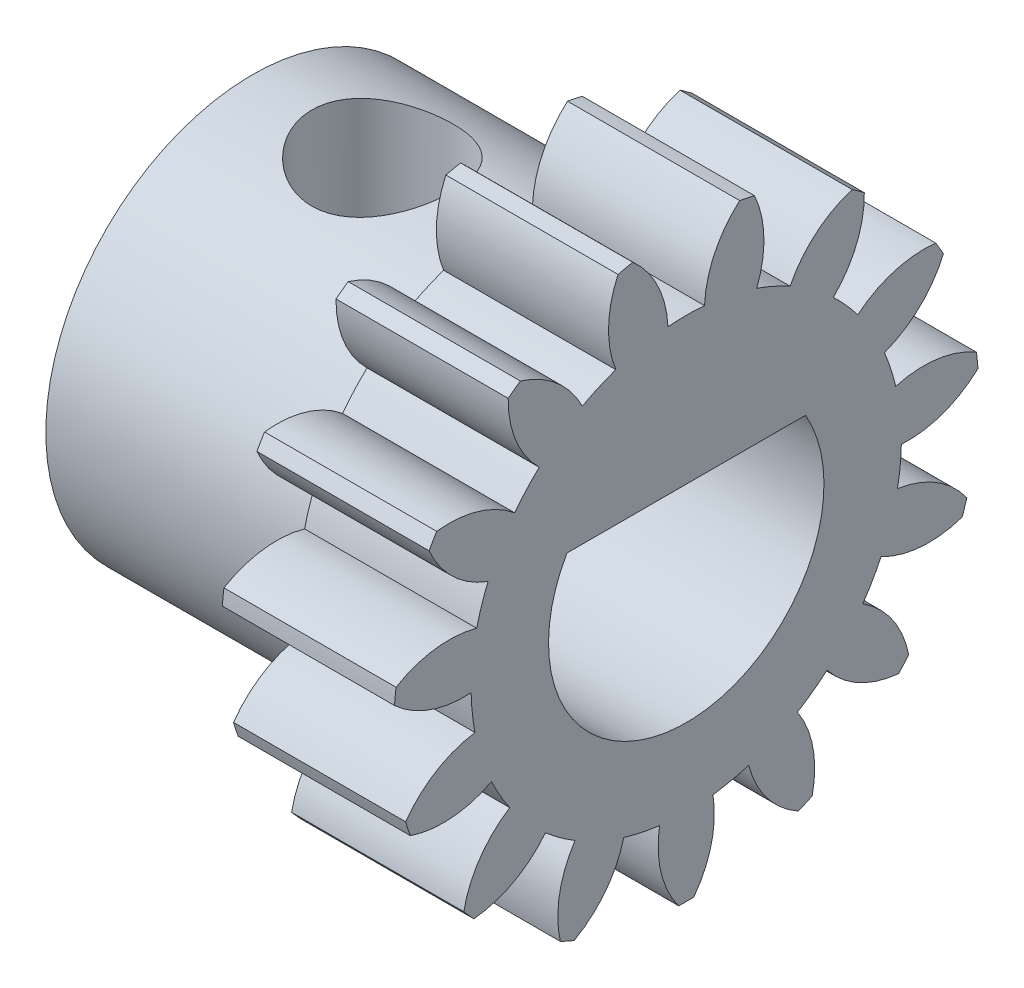
SolidWorks part; units mm, degrees
material "Plain Carbon Steel"
ref_plane "Front Plane" through (0, 0, 0) normal (0, 0, 1) x (1, 0, 0)
ref_plane "Top Plane" through (0, 0, 0) normal (0, 1, 0) x (1, 0, 0)
ref_plane "Right Plane" through (0, 0, 0) normal (1, 0, 0) x (0, 0, -1)
ref_plane "Plane1" through (0, 0, 0) normal (0, 0, -1) x (-1, 0, 0)
sketch "Sketch1" plane through (0, 0, 0) normal (0, 0, -1) x (-1, 0, 0)
  line L0 (-2.5, 4.25) -> (-2.5, 0)
  line L1 (-2.5, 0) -> (0, 0)
  line L2 (0, 0) -> (0, 4.25)
  line L3 (0, 4.25) -> (-2.5, 4.25)
  line L4 (-2.5, 0) -> (0, 0) construction
revolve "Revolve1" add sketch "Sketch1" angle 360 about L4
sketch "Sketch2" plane through (2.5, 0, 0) normal (1, 0, 0) x (0, 0, -1)
  arc A0 (2.586, 3.3727) -> (2.1353, 2.2803) centre (1.0861, 3.3523) cw
  arc A1 (2.1353, 2.2803) -> (2.491, 1.8853) centre (0, 0) cw
  arc A2 (2.491, 1.8853) -> (3.6245, 2.2193) centre (3.4475, 0.7298) cw
  arc A3 (3.6245, 2.2193) -> (2.586, 3.3727) centre (0, 0) ccw
extrude "Cut-Extrude1" cut sketch "Sketch2" against normal through all
sketch "Sketch3" plane through (2.5, 0, 0) normal (1, 0, 0) x (0, 0, -1)
  arc A0 (3.7342, 2.0293) -> (2.8782, 1.2146) centre (2.3557, 2.6207) cw
  arc A1 (2.8782, 1.2146) -> (3.0425, 0.7091) centre (0, 0) cw
  arc A2 (3.0425, 0.7091) -> (4.2138, 0.5532) centre (3.4462, -0.7355) cw
  arc A3 (4.2138, 0.5532) -> (3.7342, 2.0293) centre (0, 0) ccw
extrude "Cut-Extrude2" cut sketch "Sketch3" against normal through all
sketch "Sketch4" plane through (2.5, 0, 0) normal (1, 0, 0) x (0, 0, -1)
  arc A0 (4.2368, 0.335) -> (3.1234, -0.0611) centre (3.218, 1.436) cw
  arc A1 (3.1234, -0.0611) -> (3.0678, -0.5897) centre (0, 0) cw
  arc A2 (3.0678, -0.5897) -> (4.0745, -1.2086) centre (2.8491, -2.0736) cw
  arc A3 (4.0745, -1.2086) -> (4.2368, 0.335) centre (0, 0) ccw
extrude "Cut-Extrude3" cut sketch "Sketch4" against normal through all
sketch "Sketch5" plane through (2.5, 0, 0) normal (1, 0, 0) x (0, 0, -1)
  arc A0 (4.0067, -1.4172) -> (2.8285, -1.3262) centre (3.5238, 0.0029) cw
  arc A1 (2.8285, -1.3262) -> (2.5628, -1.7865) centre (0, 0) cw
  arc A2 (2.5628, -1.7865) -> (3.2307, -2.7613) centre (1.7594, -3.0532) cw
  arc A3 (3.2307, -2.7613) -> (4.0067, -1.4172) centre (0, 0) ccw
extrude "Cut-Extrude4" cut sketch "Sketch5" against normal through all
sketch "Sketch6" plane through (2.5, 0, 0) normal (1, 0, 0) x (0, 0, -1)
  arc A0 (3.0839, -2.9244) -> (2.0446, -2.362) centre (3.2204, -1.4306) cw
  arc A1 (2.0446, -2.362) -> (1.6146, -2.6744) centre (0, 0) cw
  arc A2 (1.6146, -2.6744) -> (1.8283, -3.8367) centre (0.3654, -3.5048) cw
  arc A3 (1.8283, -3.8367) -> (3.0839, -2.9244) centre (0, 0) ccw
extrude "Cut-Extrude5" cut sketch "Sketch6" against normal through all
sketch "Sketch7" plane through (2.5, 0, 0) normal (1, 0, 0) x (0, 0, -1)
  arc A0 (1.6279, -3.9259) -> (0.9071, -2.9894) centre (2.3601, -2.6168) cw
  arc A1 (0.9071, -2.9894) -> (0.3872, -3.0999) centre (0, 0) cw
  arc A2 (0.3872, -3.0999) -> (0.1097, -4.2486) centre (-1.0917, -3.3505) cw
  arc A3 (0.1097, -4.2486) -> (1.6279, -3.9259) centre (0, 0) ccw
extrude "Cut-Extrude6" cut sketch "Sketch7" against normal through all
sketch "Sketch8" plane through (2.5, 0, 0) normal (1, 0, 0) x (0, 0, -1)
  arc A0 (-0.1097, -4.2486) -> (-0.3872, -3.0999) centre (1.0917, -3.3505) cw
  arc A1 (-0.3872, -3.0999) -> (-0.9071, -2.9894) centre (0, 0) cw
  arc A2 (-0.9071, -2.9894) -> (-1.6279, -3.9259) centre (-2.3601, -2.6168) cw
  arc A3 (-1.6279, -3.9259) -> (-0.1097, -4.2486) centre (0, 0) ccw
extrude "Cut-Extrude7" cut sketch "Sketch8" against normal through all
sketch "Sketch9" plane through (2.5, 0, 0) normal (1, 0, 0) x (0, 0, -1)
  arc A0 (-1.8283, -3.8367) -> (-1.6146, -2.6744) centre (-0.3654, -3.5048) cw
  arc A1 (-1.6146, -2.6744) -> (-2.0446, -2.362) centre (0, 0) cw
  arc A2 (-2.0446, -2.362) -> (-3.0839, -2.9244) centre (-3.2204, -1.4306) cw
  arc A3 (-3.0839, -2.9244) -> (-1.8283, -3.8367) centre (0, 0) ccw
extrude "Cut-Extrude8" cut sketch "Sketch9" against normal through all
sketch "Sketch10" plane through (2.5, 0, 0) normal (1, 0, 0) x (0, 0, -1)
  arc A0 (-3.2307, -2.7613) -> (-2.5628, -1.7865) centre (-1.7594, -3.0532) cw
  arc A1 (-2.5628, -1.7865) -> (-2.8285, -1.3262) centre (0, 0) cw
  arc A2 (-2.8285, -1.3262) -> (-4.0067, -1.4172) centre (-3.5238, 0.0029) cw
  arc A3 (-4.0067, -1.4172) -> (-3.2307, -2.7613) centre (0, 0) ccw
extrude "Cut-Extrude9" cut sketch "Sketch10" against normal through all
sketch "Sketch11" plane through (2.5, 0, 0) normal (1, 0, 0) x (0, 0, -1)
  arc A0 (-4.0745, -1.2086) -> (-3.0678, -0.5897) centre (-2.8491, -2.0736) cw
  arc A1 (-3.0678, -0.5897) -> (-3.1234, -0.0611) centre (0, 0) cw
  arc A2 (-3.1234, -0.0611) -> (-4.2368, 0.335) centre (-3.218, 1.436) cw
  arc A3 (-4.2368, 0.335) -> (-4.0745, -1.2086) centre (0, 0) ccw
extrude "Cut-Extrude10" cut sketch "Sketch11" against normal through all
sketch "Sketch12" plane through (2.5, 0, 0) normal (1, 0, 0) x (0, 0, -1)
  arc A0 (-4.2138, 0.5532) -> (-3.0425, 0.7091) centre (-3.4462, -0.7355) cw
  arc A1 (-3.0425, 0.7091) -> (-2.8782, 1.2146) centre (0, 0) cw
  arc A2 (-2.8782, 1.2146) -> (-3.7342, 2.0293) centre (-2.3557, 2.6207) cw
  arc A3 (-3.7342, 2.0293) -> (-4.2138, 0.5532) centre (0, 0) ccw
extrude "Cut-Extrude11" cut sketch "Sketch12" against normal through all
sketch "Sketch13" plane through (2.5, 0, 0) normal (1, 0, 0) x (0, 0, -1)
  arc A0 (-2.586, 3.3727) -> (-3.6245, 2.2193) centre (0, 0) ccw
  arc A1 (-3.6245, 2.2193) -> (-2.491, 1.8853) centre (-3.4475, 0.7298) cw
  arc A2 (-2.491, 1.8853) -> (-2.1353, 2.2803) centre (0, 0) cw
  arc A3 (-2.1353, 2.2803) -> (-2.586, 3.3727) centre (-1.0861, 3.3523) cw
extrude "Cut-Extrude12" cut sketch "Sketch13" against normal through all
sketch "Sketch14" plane through (2.5, 0, 0) normal (1, 0, 0) x (0, 0, -1)
  arc A0 (-0.9906, 4.1329) -> (-2.4085, 3.5016) centre (0, 0) ccw
  arc A1 (-2.4085, 3.5016) -> (-1.5088, 2.7355) centre (-2.8526, 2.0689) cw
  arc A2 (-1.5088, 2.7355) -> (-1.0232, 2.9517) centre (0, 0) cw
  arc A3 (-1.0232, 2.9517) -> (-0.9906, 4.1329) centre (0.3713, 3.5042) cw
extrude "Cut-Extrude13" cut sketch "Sketch14" against normal through all
sketch "Sketch15" plane through (2.5, 0, 0) normal (1, 0, 0) x (0, 0, -1)
  arc A0 (-0.776, 4.1785) -> (-0.2658, 3.1127) centre (-1.7645, 3.0503) cw
  arc A1 (-0.2658, 3.1127) -> (0.2658, 3.1127) centre (0, 0) cw
  arc A2 (0.2658, 3.1127) -> (0.776, 4.1785) centre (1.7645, 3.0503) cw
  arc A3 (0.776, 4.1785) -> (-0.776, 4.1785) centre (0, 0) ccw
extrude "Cut-Extrude14" cut sketch "Sketch15" against normal through all
sketch "Sketch16" plane through (2.5, 0, 0) normal (1, 0, 0) x (0, 0, -1)
  arc A0 (0.9906, 4.1329) -> (1.0232, 2.9517) centre (-0.3713, 3.5042) cw
  arc A1 (1.0232, 2.9517) -> (1.5088, 2.7355) centre (0, 0) cw
  arc A2 (1.5088, 2.7355) -> (2.4085, 3.5016) centre (2.8526, 2.0689) cw
  arc A3 (2.4085, 3.5016) -> (0.9906, 4.1329) centre (0, 0) ccw
extrude "Cut-Extrude15" cut sketch "Sketch16" against normal through all
sketch "Sketch17" plane through (0, 0, 0) normal (0, 0, 1) x (1, 0, 0)
  line L0 (-3.8001, 3) -> (-3.8001, 0)
  line L1 (-3.8001, 0) -> (0, 0)
  line L2 (0, 0) -> (0, 3)
  line L3 (0, 3) -> (-3.8001, 3)
  line L4 (-3.8001, 0) -> (0, 0) construction
revolve "Revolve2" add sketch "Sketch17" angle 360 about L4
hole_wizard "Ø4.0 (4) Diameter Hole1" positions "Sketch19" profile "Sketch18" hole size "Ø4.0" standard "ANSI Metric"
sketch "Sketch19" plane through (2.5, 0, 0) normal (1, 0, 0) x (0, 0, -1)
  point P0 (0, 0)
sketch "Sketch18" plane through (2.5, 0, 0) normal (0, 1, 0) x (0, 0, -1)
  line L0 (0, 0) -> (0, 6.3001)
  line L1 (0, 6.3001) -> (2, 6.3001)
  line L2 (2, 6.3001) -> (2, 0)
  line L5 (2, 0) -> (0, 0)
  line L11 (0, -6.35) -> (0, 107.95) construction
  dimension "Thru Hole Dia." = 4
  dimension "Thru Hole Depth" = 6.3001
sketch "Sketch21" plane through (-3.8001, 0, 0) normal (-1, 0, 0) x (0, 0, 1)
  line L0 (-1.7321, 1) -> (1.7321, 1)
  arc A0 (1.7321, 1) -> (-1.7321, 1) centre (0, 0) ccw
  circle A1 centre (0, 0) radius 2 construction
  dimension "D1" = 1
extrude "Boss-Extrude2" add sketch "Sketch21" against normal up to surface (6.3001 mm away) up to face at (2.5, 0, -2)
hole_wizard "Tap Drill for M2.5x0.45 Tap1" positions "3DSketch1" profile "Sketch20" hole size "M2.5x0.45" standard "ANSI Metric"
sketch3d "3DSketch1"
  point P0 (-1.9001, 3, 0.0133)
sketch "Sketch20" plane through (-1.9001, 3, 0.0133) normal (1, 0, 0) x (0, -0.0044, 1)
  line L0 (0, 0) -> (0, 3)
  line L1 (0, 3) -> (1.025, 3)
  line L2 (1.025, 3) -> (1.025, 0)
  line L5 (1.025, 0) -> (0, 0)
  line L10 (0, 3) -> (-1.025, 3) construction
  line L11 (0, -6.35) -> (0, 107.95) construction
  dimension "Hole Dia." = 2.05
  dimension "Hole Depth" = 3
  dimension "Drill Angle" = 180
